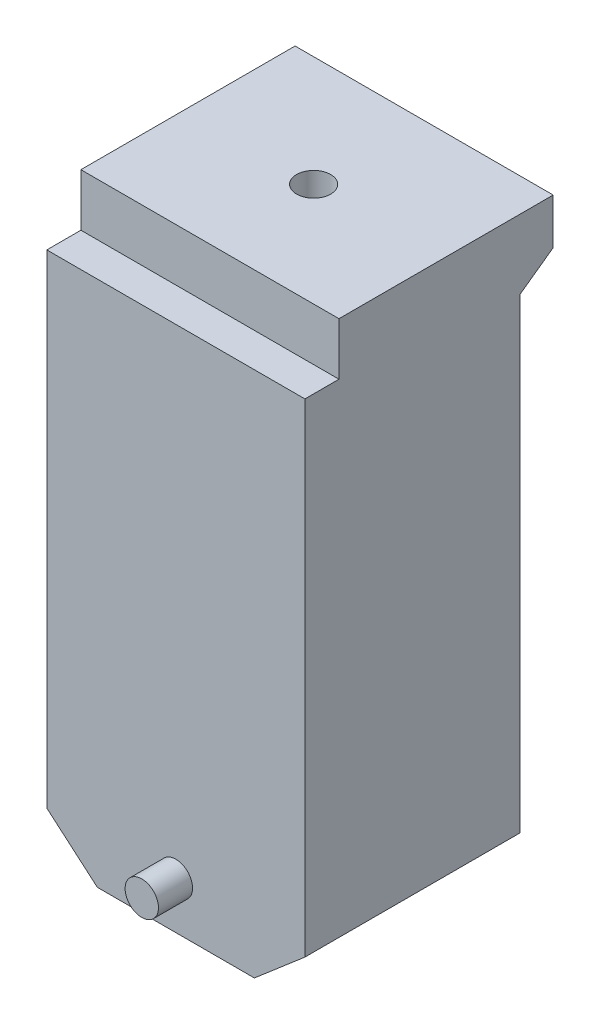
SolidWorks part; units mm, degrees
ref_plane "Front Plane" through (0, 0, 0) normal (0, 0, 1) x (1, 0, 0)
ref_plane "Top Plane" through (0, 0, 0) normal (0, 1, 0) x (1, 0, 0)
ref_plane "Right Plane" through (0, 0, 0) normal (1, 0, 0) x (0, 0, -1)
sketch "Sketch1" plane through (0, 0, 0) normal (1, 0, 0) x (0, 0, -1)
  line L0 (-47.6154, 84.1347) -> (-39.6154, 84.1347) construction
  line L1 (-39.6154, 97.5247) -> (15.5046, 97.5247)
  line L2 (-47.6154, 84.1347) -> (-47.6154, -72.4753)
  line L3 (-47.6154, -72.4753) -> (15.5046, -72.4753)
  line L4 (15.5046, 77.1347) -> (15.5046, -72.4753)
  line L5 (-39.6154, 97.5247) -> (-39.6154, 84.1347)
  line L7 (15.5046, 97.5247) -> (25.2546, 97.5247)
  line L8 (25.2546, 97.5247) -> (25.2546, 84.1347)
  line L9 (25.2546, 84.1347) -> (15.5046, 77.1347)
  line L10 (-47.6154, 84.1347) -> (-39.6154, 84.1347)
  dimension "D1" = 8
  dimension "D2" = 63.12
  dimension "D3" = 64.8699
  dimension "D5" = 13.39
  dimension "D6" = 20.39
extrude "Boss-Extrude1" add sketch "Sketch1" along normal blind 75.75
sketch "Sketch2" plane through (0, 0, 47.6154) normal (0, 0, 1) x (1, 0, 0)
  line L1 (0, 84.1347) -> (0, -72.4753) construction
  line L2 (75.75, 84.1347) -> (75.75, -72.4753) construction
  line L5 (0, -59.7553) -> (14.83, -72.4753)
  line L6 (75.75, -72.4753) -> (0, -72.4753) construction
  line L9 (75.75, -59.7553) -> (60.92, -72.4753)
  line L10 (60.92, -72.4753) -> (75.75, -72.4753)
  line L11 (75.75, -72.4753) -> (75.75, -59.7553)
  line L12 (14.83, -72.4753) -> (0, -72.4753)
  line L13 (0, -72.4753) -> (0, -59.7553)
  dimension "D1" = 12.72
extrude "Cut-Extrude1" cut sketch "Sketch2" against normal through all
sketch "Sketch3" plane through (0, 0, 47.6154) normal (0, 0, 1) x (1, 0, 0)
  line L0 (0, -58.7053) -> (75.75, -58.7053) construction
  line L1 (0, 84.1347) -> (0, -59.7553) construction
  line L2 (75.75, 84.1347) -> (75.75, -59.7553) construction
  line L3 (37.875, -58.7053) -> (37.875, -72.4753) construction
  line L4 (60.92, -72.4753) -> (14.83, -72.4753) construction
  circle A0 centre (37.875, -58.7053) radius 4.9
  dimension "D1" = 13.77
extrude "Boss-Extrude2" add sketch "Sketch3" along normal blind 10 and the other way blind 73.12
sketch "Sketch4" plane through (0, 97.5247, 0) normal (0, 1, 0) x (1, 0, 0)
  line L0 (0, 25.2546) -> (75.75, -39.6154) construction
  circle A0 centre (37.875, -7.1804) radius 5
extrude "Cut-Extrude2" cut sketch "Sketch4" against normal blind 10
sketch "Sketch5" plane through (75.75, 0, 0) normal (1, 0, 0) x (0, 0, -1)
  line L1 (-39.6154, 97.5247) -> (-37.6154, 97.5247)
  line L2 (-39.6154, 97.5247) -> (-39.6154, 84.1347)
  line L3 (-39.6154, 84.1347) -> (-37.6154, 84.1347)
  line L4 (-37.6154, 97.5247) -> (-37.6154, 84.1347)
  dimension "D1" = 2
extrude "Cut-Extrude3" cut sketch "Sketch5" against normal through all
sketch "Sketch6" plane through (75.75, 0, 0) normal (1, 0, 0) x (0, 0, -1)
  line L1 (-47.6154, 84.1347) -> (-37.6154, 84.1347)
  line L2 (-47.6154, 84.1347) -> (-47.6154, 82.1347)
  line L3 (-47.6154, 82.1347) -> (-37.6154, 82.1347)
  line L4 (-37.6154, 84.1347) -> (-37.6154, 82.1347)
  dimension "D1" = 10
  dimension "D2" = 2
extrude "Cut-Extrude4" cut sketch "Sketch6" against normal through all
